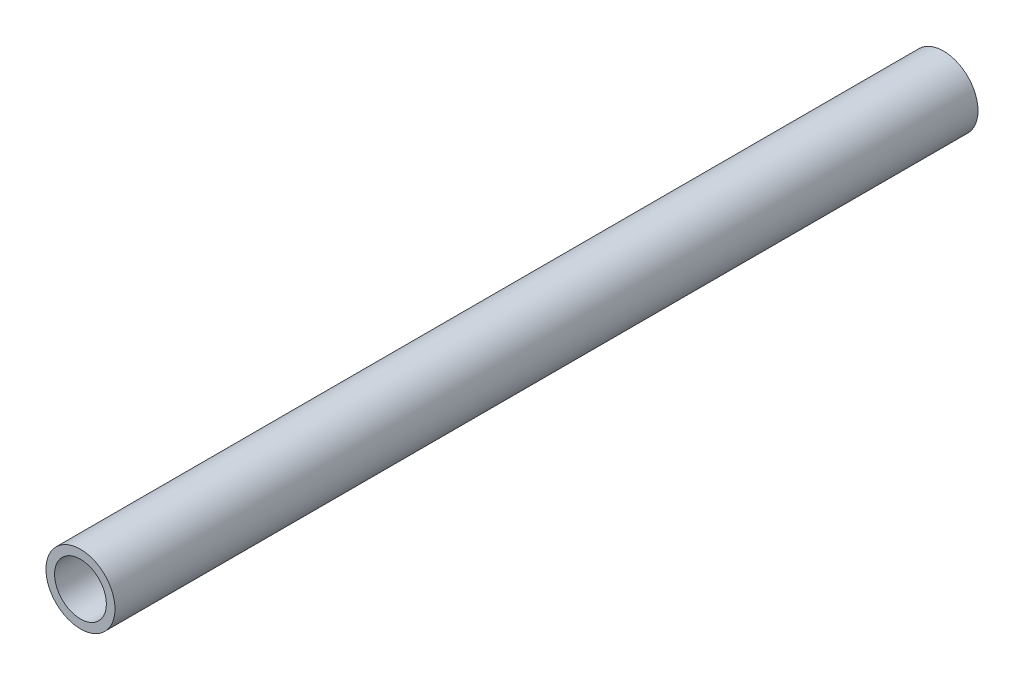
SolidWorks part; units mm, degrees
material "Thornel Mat VMA"
ref_plane "Front Plane" through (0, 0, 0) normal (0, 0, 1) x (1, 0, 0)
ref_plane "Top Plane" through (0, 0, 0) normal (0, 1, 0) x (1, 0, 0)
ref_plane "Right Plane" through (0, 0, 0) normal (1, 0, 0) x (0, 0, -1)
sketch "Sketch1" plane through (0, 0, 0) normal (0, 0, 1) x (1, 0, 0)
  circle A0 centre (0, 0) radius 3
  circle A1 centre (0, 0) radius 4
  dimension "D1" = 6
  dimension "D2" = 8
extrude "Boss-Extrude1" add sketch "Sketch1" along normal blind 100
